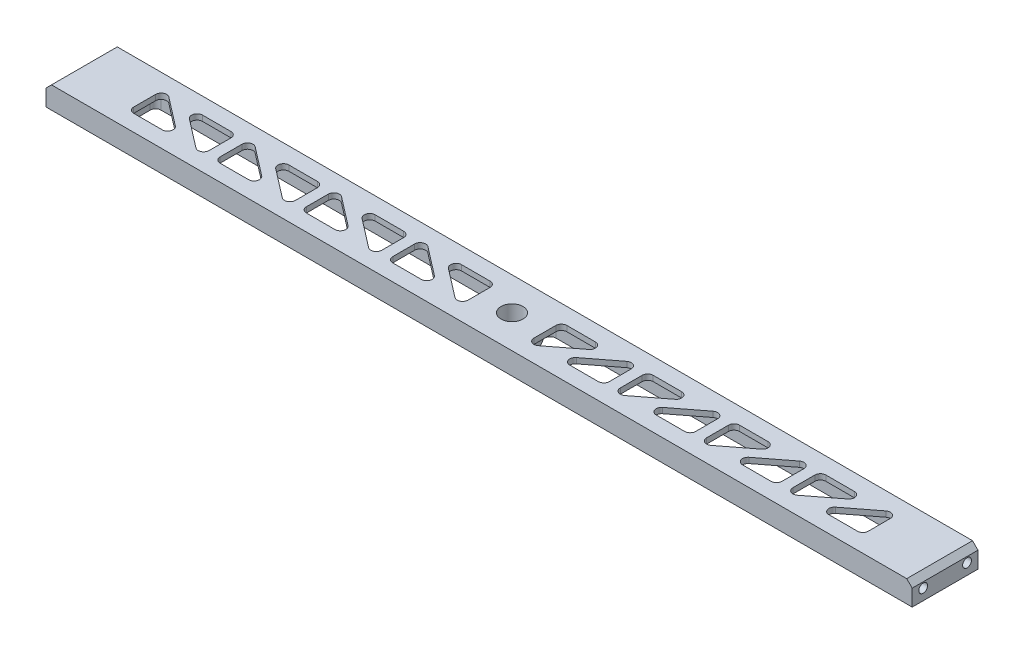
SolidWorks part; units mm, degrees
material "6061 Alloy"
ref_plane "Front Plane" through (0, 0, 0) normal (0, 0, 1) x (1, 0, 0)
ref_plane "Top Plane" through (0, 0, 0) normal (0, 1, 0) x (1, 0, 0)
ref_plane "Right Plane" through (0, 0, 0) normal (1, 0, 0) x (0, 0, -1)
sketch "Sketch1" plane through (0, 0, 0) normal (1, 0, 0) x (0, 0, -1)
  line L1 (-19.05, -6.35) -> (19.05, -6.35)
  line L2 (-19.05, -6.35) -> (-19.05, 6.35)
  line L3 (-19.05, 6.35) -> (19.05, 6.35)
  line L4 (19.05, -6.35) -> (19.05, 6.35)
  line L5 (-19.05, -6.35) -> (19.05, 6.35) construction
  line L6 (-19.05, 6.35) -> (19.05, -6.35) construction
  point P0 (0, 0)
  dimension "D1" = 38.1
  dimension "D2" = 12.7
extrude "Boss-Extrude1" add sketch "Sketch1" along normal mid plane 501.65
sketch "Sketch2" plane through (0, 6.35, 0) normal (0, 1, 0) x (1, 0, 0)
  circle A0 centre (0, 0) radius 6.35
  dimension "D1" = 12.7
extrude "Cut-Extrude1" cut sketch "Sketch2" against normal through all
hole_wizard "1/4-20 Tapped Hole1" positions "3DSketch1" profile "Sketch3" tap size "1/4-20" standard "ANSI Inch"
sketch3d "3DSketch1"
  line L4 (250.825, 0, 19.05) -> (250.825, 0, 12.7) construction
  line L5 (250.825, 6.35, 19.05) -> (250.825, -6.35, 19.05) construction
  line L6 (250.825, 0, 12.7) -> (250.825, 0, -12.7) construction
  line L7 (250.825, 0, -12.7) -> (250.825, 0, -19.05) construction
  line L8 (250.825, -6.35, -19.05) -> (250.825, 6.35, -19.05) construction
  point P0 (250.825, 0, 12.7)
  point P2 (250.825, 0, -12.7)
  dimension "D1" = 25.4
sketch "Sketch3" plane through (250.825, 0, 12.7) normal (0, 1, 0) x (0, 0, -1)
  line L0 (0, 0) -> (0, 30.7438)
  line L1 (0, 30.7438) -> (2.5527, 29.21)
  line L2 (2.5527, 29.21) -> (2.5527, 0)
  line L5 (2.5527, 0) -> (0, 0)
  line L10 (0, 30.7438) -> (-2.5527, 29.21) construction
  line L11 (0, -6.35) -> (0, 107.95) construction
  dimension "Tap Drill Dia." = 5.1054
  dimension "Tap Drill Depth" = 29.21
  dimension "Drill Angle" = 118
chamfer "Chamfer1" distance 3.175 2 edges at (250.825, 6.35, 0) (-250.825, 6.35, 0)
sketch "Sketch4" plane through (0, -6.35, 0) normal (0, -1, 0) x (1, 0, 0)
  line L0 (-250.825, 19.05) -> (-250.825, -19.05) construction
  line L1 (-215.9, -12.7) -> (-12.7, -12.7)
  line L2 (-219.075, -9.525) -> (-219.075, 9.525)
  line L3 (-215.9, 12.7) -> (-12.7, 12.7)
  line L4 (219.075, -9.525) -> (219.075, 9.525)
  line L5 (-219.075, -12.7) -> (219.075, 12.7) construction
  line L6 (-219.075, 12.7) -> (219.075, -12.7) construction
  line L7 (250.825, 19.05) -> (-250.825, 19.05) construction
  line L8 (12.7, 12.7) -> (215.9, 12.7)
  line L9 (12.7, -12.7) -> (215.9, -12.7)
  arc A0 (215.9, 12.7) -> (219.075, 9.525) centre (215.9, 9.525) cw
  arc A1 (215.9, -12.7) -> (219.075, -9.525) centre (215.9, -9.525) ccw
  arc A2 (-215.9, -12.7) -> (-219.075, -9.525) centre (-215.9, -9.525) cw
  arc A3 (-219.075, 9.525) -> (-215.9, 12.7) centre (-215.9, 9.525) cw
  arc A4 (-10.16, 7.62) -> (-10.16, -7.62) centre (0, 0) ccw
  arc A5 (-12.7, 12.7) -> (-10.16, 7.62) centre (-12.7, 9.525) cw
  arc A6 (10.16, 7.62) -> (12.7, 12.7) centre (12.7, 9.525) cw
  arc A7 (10.16, -7.62) -> (12.7, -12.7) centre (12.7, -9.525) ccw
  arc A8 (-10.16, -7.62) -> (-12.7, -12.7) centre (-12.7, -9.525) cw
  arc A9 (10.16, -7.62) -> (10.16, 7.62) centre (0, 0) ccw
  point P0 (0, 0)
  dimension "D3" = 3.175
  dimension "D4" = 3.175
  dimension "D1" = 31.75
  dimension "D2" = 6.35
extrude "Cut-Extrude2" cut sketch "Sketch4" against normal blind 9.525
sketch "Sketch5" plane through (0, 3.175, 0) normal (0, -1, 0) x (1, 0, 0)
  line L0 (-212.725, 6.35) -> (-212.725, -6.35)
  line L1 (-207.6128, -8.8655) -> (-191.1214, 3.8345)
  line L2 (-193.0586, 9.525) -> (-209.55, 9.525)
  line L3 (-190.6724, -3.8345) -> (-174.181, 8.8655)
  line L4 (-169.0688, 6.35) -> (-169.0688, -6.35)
  line L5 (-172.2438, -9.525) -> (-188.7352, -9.525)
  line L6 (-219.075, 0) -> (-212.725, 0) construction
  line L7 (-219.075, 9.525) -> (-219.075, -9.525) construction
  line L8 (-12.7, 12.7) -> (-215.9, 12.7) construction
  line L9 (-215.9, -12.7) -> (-12.7, -12.7) construction
  line L10 (-191.1214, 3.8345) -> (-187.247, -1.1966) construction
  line L11 (-119.0625, 6.35) -> (-119.0625, -6.35)
  line L12 (-140.6661, -3.8345) -> (-124.1747, 8.8655)
  line L13 (-122.2375, -9.525) -> (-138.7289, -9.525)
  line L14 (-141.1151, 3.8345) -> (-137.2407, -1.1966) construction
  line L15 (-143.0523, 9.525) -> (-159.5438, 9.525)
  line L16 (-162.7188, 6.35) -> (-162.7188, -6.35)
  line L17 (-157.6065, -8.8655) -> (-141.1151, 3.8345)
  line L18 (-169.0688, 0) -> (-162.7188, 0) construction
  line L19 (-69.0563, 6.35) -> (-69.0563, -6.35)
  line L20 (-90.6599, -3.8345) -> (-74.1685, 8.8655)
  line L21 (-72.2313, -9.525) -> (-88.7227, -9.525)
  line L22 (-91.1089, 3.8345) -> (-87.2345, -1.1966) construction
  line L23 (-93.0461, 9.525) -> (-109.5375, 9.525)
  line L24 (-112.7125, 6.35) -> (-112.7125, -6.35)
  line L25 (-107.6003, -8.8655) -> (-91.1089, 3.8345)
  line L26 (-119.0625, 0) -> (-112.7125, 0) construction
  line L27 (-19.05, 6.35) -> (-19.05, -6.35)
  line L28 (-40.6536, -3.8345) -> (-24.1622, 8.8655)
  line L29 (-22.225, -9.525) -> (-38.7164, -9.525)
  line L30 (-41.1026, 3.8345) -> (-37.2282, -1.1966) construction
  line L31 (-43.0398, 9.525) -> (-59.5313, 9.525)
  line L32 (-62.7063, 6.35) -> (-62.7062, -6.35)
  line L33 (-57.594, -8.8655) -> (-41.1026, 3.8345)
  line L34 (-69.0563, 0) -> (-62.7063, 0) construction
  line L35 (-12.7, 0) -> (-19.05, 0) construction
  arc A0 (-174.181, 8.8655) -> (-169.0688, 6.35) centre (-172.2438, 6.35) cw
  arc A1 (-169.0688, -6.35) -> (-172.2438, -9.525) centre (-172.2438, -6.35) cw
  arc A2 (-190.6724, -3.8345) -> (-188.7352, -9.525) centre (-188.7352, -6.35) ccw
  arc A3 (-212.725, -6.35) -> (-207.6128, -8.8655) centre (-209.55, -6.35) ccw
  arc A4 (-191.1214, 3.8345) -> (-193.0586, 9.525) centre (-193.0586, 6.35) ccw
  arc A5 (-212.725, 6.35) -> (-209.55, 9.525) centre (-209.55, 6.35) cw
  arc A6 (-124.1747, 8.8655) -> (-119.0625, 6.35) centre (-122.2375, 6.35) cw
  arc A7 (-140.6661, -3.8345) -> (-138.7289, -9.525) centre (-138.7289, -6.35) ccw
  arc A8 (-119.0625, -6.35) -> (-122.2375, -9.525) centre (-122.2375, -6.35) cw
  arc A9 (-141.1151, 3.8345) -> (-143.0523, 9.525) centre (-143.0523, 6.35) ccw
  arc A10 (-162.7188, 6.35) -> (-159.5438, 9.525) centre (-159.5438, 6.35) cw
  arc A11 (-162.7188, -6.35) -> (-157.6065, -8.8655) centre (-159.5438, -6.35) ccw
  arc A12 (-74.1685, 8.8655) -> (-69.0563, 6.35) centre (-72.2313, 6.35) cw
  arc A13 (-90.6599, -3.8345) -> (-88.7227, -9.525) centre (-88.7227, -6.35) ccw
  arc A14 (-69.0563, -6.35) -> (-72.2313, -9.525) centre (-72.2313, -6.35) cw
  arc A15 (-91.1089, 3.8345) -> (-93.0461, 9.525) centre (-93.0461, 6.35) ccw
  arc A16 (-112.7125, 6.35) -> (-109.5375, 9.525) centre (-109.5375, 6.35) cw
  arc A17 (-112.7125, -6.35) -> (-107.6003, -8.8655) centre (-109.5375, -6.35) ccw
  arc A18 (-24.1622, 8.8655) -> (-19.05, 6.35) centre (-22.225, 6.35) cw
  arc A19 (-40.6536, -3.8345) -> (-38.7164, -9.525) centre (-38.7164, -6.35) ccw
  arc A20 (-19.05, -6.35) -> (-22.225, -9.525) centre (-22.225, -6.35) cw
  arc A21 (-41.1026, 3.8345) -> (-43.0398, 9.525) centre (-43.0398, 6.35) ccw
  arc A22 (-62.7063, 6.35) -> (-59.5313, 9.525) centre (-59.5313, 6.35) cw
  arc A23 (-62.7062, -6.35) -> (-57.594, -8.8655) centre (-59.5313, -6.35) ccw
  arc A24 (-10.16, 7.62) -> (-10.16, -7.62) centre (0, 0) ccw construction
  point P18 (-172.2438, 9.525)
  point P19 (-209.55, -9.525)
  dimension "D1" = 3.175
  dimension "D2" = 3.175
  dimension "D3" = 3.175
  dimension "D4" = 6.35
  dimension "D5" = 4
extrude "Cut-Extrude3" cut sketch "Sketch5" against normal through all
mirror "Mirror1" about plane through (0, 0, 0) normal (1, 0, 0) of "1/4-20 Tapped Hole1", "Cut-Extrude3"
